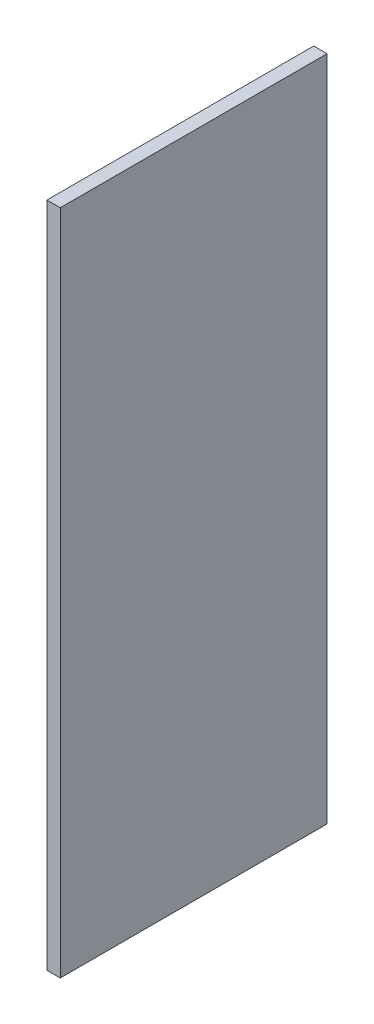
SolidWorks part; units mm, degrees
ref_plane "Front Plane" through (0, 0, 0) normal (0, 0, 1) x (1, 0, 0)
ref_plane "Top Plane" through (0, 0, 0) normal (0, 1, 0) x (1, 0, 0)
ref_plane "Right Plane" through (0, 0, 0) normal (1, 0, 0) x (0, 0, -1)
sketch "Sketch1" plane through (0, 0, 0) normal (1, 0, 0) x (0, 0, -1)
  line L0 (0, 0) -> (0, 52.6316) construction
  line L1 (-10, 0) -> (10, 0)
  line L2 (-10, 0) -> (-10, 50)
  line L3 (-10, 50) -> (10, 50)
  line L4 (10, 0) -> (10, 50)
  dimension "D1" = 20
  dimension "D2" = 50
extrude "Boss-Extrude1" add sketch "Sketch1" along normal blind 1
